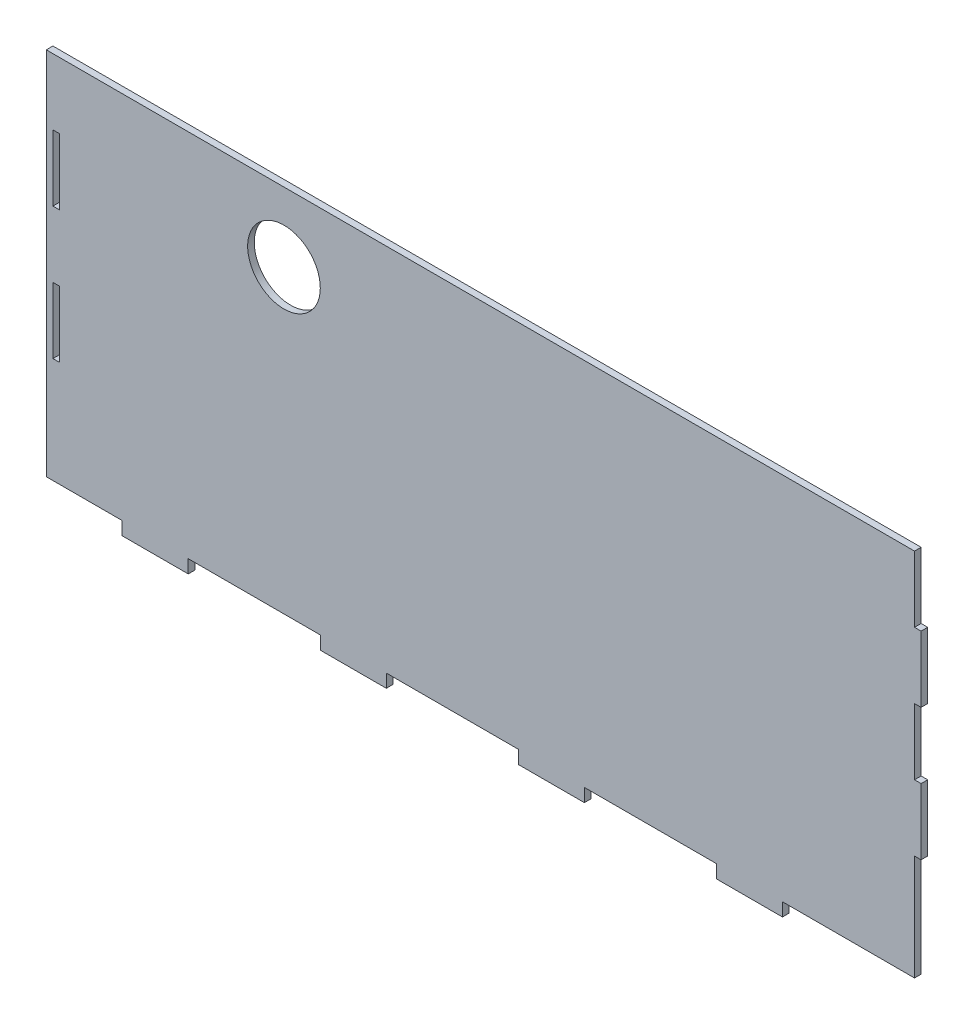
SolidWorks part; units mm, degrees
ref_plane "Front Plane" through (0, 0, 0) normal (0, 0, 1) x (1, 0, 0)
ref_plane "Top Plane" through (0, 0, 0) normal (0, 1, 0) x (1, 0, 0)
ref_plane "Right Plane" through (0, 0, 0) normal (1, 0, 0) x (0, 0, -1)
sketch "Sketch1" plane through (0, 0, 0) normal (0, 0, 1) x (1, 0, 0)
  line L0 (11.5, -56) -> (11.5, -60)
  line L1 (-131.5, -56) -> (-108.5, -56)
  line L2 (-131.5, -56) -> (-131.5, -24)
  line L3 (-131.5, 56) -> (131.5, 56)
  line L4 (131.5, -56) -> (131.5, -24)
  line L5 (-131.5, -56) -> (131.5, 56) construction
  line L6 (-131.5, 56) -> (131.5, -56) construction
  line L8 (71.5, -56) -> (71.5, -60)
  line L9 (71.5, -60) -> (91.5, -60)
  line L10 (91.5, -56) -> (91.5, -60)
  line L12 (31.5, -56) -> (31.5, -60)
  line L13 (11.5, -60) -> (31.5, -60)
  line L14 (-48.5, -56) -> (-48.5, -60)
  line L16 (-28.5, -56) -> (-28.5, -60)
  line L17 (-48.5, -60) -> (-28.5, -60)
  line L18 (-108.5, -56) -> (-108.5, -60)
  line L20 (-88.5, -56) -> (-88.5, -60)
  line L21 (-108.5, -60) -> (-88.5, -60)
  line L22 (-88.5, -56) -> (-48.5, -56)
  line L24 (131.5, 36) -> (133.5, 36)
  line L25 (-28.5, -56) -> (11.5, -56)
  line L27 (31.5, -56) -> (71.5, -56)
  line L28 (91.5, -56) -> (131.5, -56)
  line L29 (131.5, 16) -> (133.5, 16)
  line L30 (133.5, 36) -> (133.5, 16)
  line L31 (131.5, -4) -> (133.5, -4)
  line L32 (133.5, -4) -> (133.5, -24)
  line L33 (131.5, -24) -> (133.5, -24)
  line L34 (131.5, 36) -> (131.5, 56)
  line L35 (131.5, -4) -> (131.5, 16)
  line L44 (-131.5, 36) -> (-131.5, 16)
  line L73 (-131.5, 36) -> (-131.5, 56)
  line L78 (-131.5, -4) -> (-131.5, 16)
  line L79 (-131.5, -4) -> (-131.5, -24)
  circle A0 centre (-59.5, 35) radius 11
  point P0 (0, 0)
  dimension "D5" = 22
  dimension "D1" = 263
  dimension "D2" = 112
  dimension "D3" = 72
  dimension "D4" = 21
  dimension "D6" = 4
  dimension "D7" = 40
  dimension "D8" = 20
  dimension "D10" = 40
  dimension "D11" = 20
  dimension "D12" = 20
  dimension "D13" = 2
  dimension "D15" = 20
  dimension "D9" = 4
  dimension "D14" = 2
extrude "Boss-Extrude1" add sketch "Sketch1" along normal blind 2
sketch "Sketch2" plane through (0, 0, 2) normal (0, 0, 1) x (1, 0, 0)
  line L0 (-131.5, 56) -> (-131.5, -56) construction
  line L1 (-129.5, 16) -> (-127.5, 16)
  line L2 (-129.5, 16) -> (-129.5, 36)
  line L3 (-129.5, 36) -> (-127.5, 36)
  line L4 (-127.5, 16) -> (-127.5, 36)
  line L5 (-129.5, 16) -> (-127.5, 36) construction
  line L6 (-129.5, 36) -> (-127.5, 16) construction
  line L8 (131.5, 56) -> (-131.5, 56) construction
  line L9 (-129.5, -24) -> (-129.5, -4)
  line L10 (-129.5, -24) -> (-127.5, -24)
  line L11 (-127.5, -24) -> (-127.5, -4)
  line L12 (-129.5, -4) -> (-127.5, -4)
  point P0 (-128.5, 26)
  dimension "D1" = 20
  dimension "D2" = 2
  dimension "D3" = 2
  dimension "D4" = 20
  dimension "D6" = 20
  dimension "D5" = 2
extrude "Cut-Extrude1" cut sketch "Sketch2" against normal blind 10
sketch "Sketch4" plane through (0, 0, 2) normal (0, 0, 1) x (1, 0, 0)
  line L5 (-131.5, 56) -> (-131.5, -56) construction
  line L6 (-131.5, 41) -> (-129.5, 41)
  line L7 (-131.5, 41) -> (-131.5, 21)
  line L8 (-131.5, 21) -> (-129.5, 21)
  line L9 (-129.5, 41) -> (-129.5, 21)
  line L10 (131.5, 56) -> (-131.5, 56) construction
  dimension "D1" = 20
  dimension "D2" = 2
  dimension "D3" = 15
extrude "Cut-Extrude2" [suppressed] cut sketch "Sketch4" against normal blind 10
